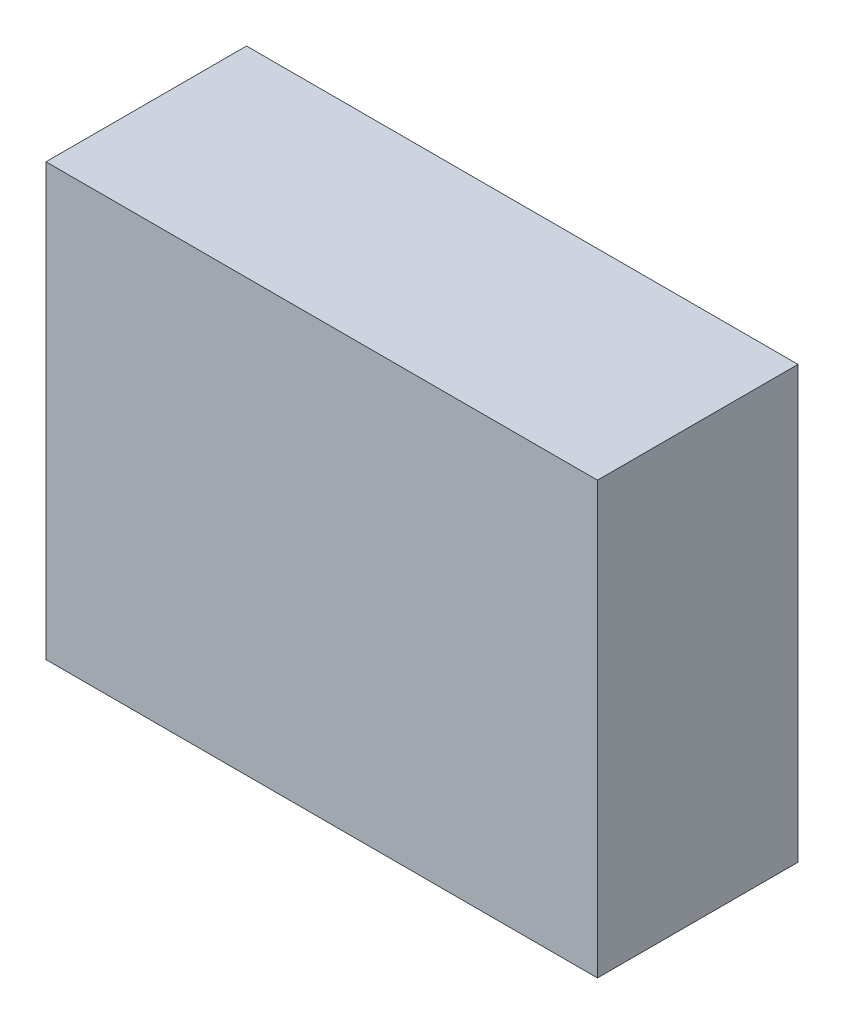
SolidWorks part; units mm, degrees
ref_plane "前视基准面" through (0, 0, 0) normal (0, 0, 1) x (1, 0, 0)
ref_plane "上视基准面" through (0, 0, 0) normal (0, 1, 0) x (1, 0, 0)
ref_plane "右视基准面" through (0, 0, 0) normal (1, 0, 0) x (0, 0, -1)
other "Configuration Table"
sketch "草图1" plane through (0, 0, 0) normal (0, 0, 1) x (1, 0, 0)
  line L1 (-25, -20) -> (30, -20)
  line L2 (-25, -20) -> (-25, 23)
  line L3 (-25, 23) -> (30, 23)
  line L4 (30, -20) -> (30, 23)
extrude "凸台-拉伸1" add sketch "草图1" along normal blind 20
